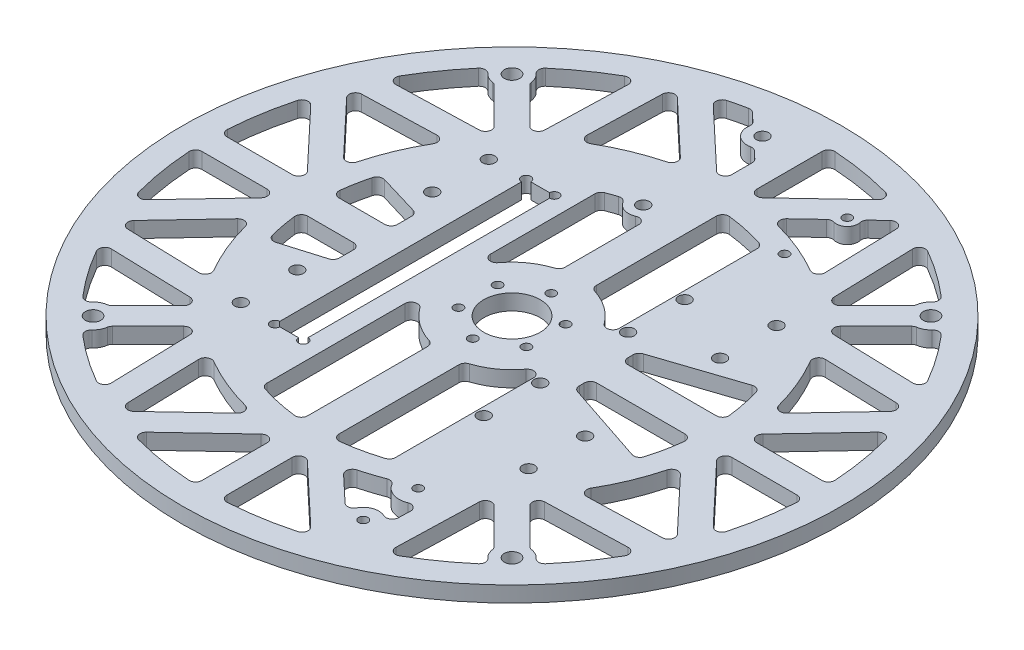
SolidWorks part; units mm, degrees
material "Thornel Mat VMA"
ref_plane "前视基准面" through (0, 0, 0) normal (0, 0, 1) x (1, 0, 0)
ref_plane "上视基准面" through (0, 0, 0) normal (0, 1, 0) x (1, 0, 0)
ref_plane "右视基准面" through (0, 0, 0) normal (1, 0, 0) x (0, 0, -1)
other "Configuration Table"
sketch "草图1" plane through (0, 0, 0) normal (0, 1, 0) x (1, 0, 0)
  circle A0 centre (0, 0) radius 105
  dimension "D1" = 210
extrude "凸台-拉伸1" add sketch "草图1" along normal blind 5
sketch "草图3" plane through (0, 5, 0) normal (0, 1, 0) x (1, 0, 0)
  circle A0 centre (-46.9, -39.5) radius 1.95
  circle A1 centre (-46.9, -21.5) radius 1.95
  circle A2 centre (-46.9, 21.5) radius 1.95
  circle A3 centre (-46.9, 39.5) radius 1.95
  circle A4 centre (23, -32) radius 1.95
  circle A5 centre (23, -14) radius 1.95
  circle A6 centre (44.8, -39.5) radius 1.95
  circle A7 centre (44.8, -21.5) radius 1.95
  circle A8 centre (44.8, 39.5) radius 1.95
  circle A9 centre (44.8, 21.5) radius 1.95
  circle A10 centre (23, 32) radius 1.95
  circle A11 centre (23, 14) radius 1.95
  circle A12 centre (-9.7, 89.516) radius 1.95
  circle A13 centre (-9.7, 51.516) radius 1.95
  circle A14 centre (26.3, 80.516) radius 1.45
  circle A15 centre (32.6, -62.5) radius 1.45
  circle A16 centre (32.6, -80) radius 1.45
  circle A17 centre (26.3, 60.516) radius 1.45
  dimension "D1" = 3.9
  dimension "D2" = 2.9
extrude "切除-拉伸1" cut sketch "草图3" against normal through all
sketch "草图5" plane through (0, 5, 0) normal (0, 1, 0) x (1, 0, 0)
  line L0 (0, 0) -> (0, 105) construction
  circle A0 centre (0, 0) radius 105 construction
sketch "草图6" plane through (0, 0, 0) normal (0, -1, 0) x (1, 0, 0)
  line L1 (-35.5, 40) -> (-26.5, 40)
  line L2 (-35.5, 40) -> (-35.5, -40)
  line L3 (-35.5, -40) -> (-26.5, -40)
  line L4 (-26.5, 40) -> (-26.5, -40)
  point P4 (-26.5, 0)
  dimension "D1" = 9
  dimension "D2" = 80
  dimension "D3" = 26.5
extrude "切除-拉伸2" cut sketch "草图6" against normal through all
sketch "草图7" plane through (0, 5, 0) normal (0, 1, 0) x (1, 0, 0)
  line L0 (0, 0) -> (66.7403, 66.7403) construction
  line L1 (0, 0) -> (94.385, 0) construction
  circle A0 centre (0, 0) radius 94.385 construction
  circle A1 centre (66.7403, 66.7403) radius 2.45
  circle A2 centre (-66.7403, 66.7403) radius 2.45
  circle A3 centre (-66.7403, -66.7403) radius 2.45
  circle A4 centre (66.7403, -66.7403) radius 2.45
  point P15 (0, 0)
  dimension "D2" = 4.9
  dimension "D4" = 188.77
  dimension "D1" = 45
  dimension "D3" = 4
extrude "切除-拉伸3" cut sketch "草图7" against normal through all
sketch "草图8" plane through (0, 5, 0) normal (0, 1, 0) x (1, 0, 0)
  circle A0 centre (0, 0) radius 12.5 construction
  circle A1 centre (0, 12.5) radius 1.45
  circle A2 centre (10.8253, 6.25) radius 1.45
  circle A3 centre (10.8253, -6.25) radius 1.45
  circle A4 centre (0, -12.5) radius 1.45
  circle A5 centre (-10.8253, -6.25) radius 1.45
  circle A6 centre (-10.8253, 6.25) radius 1.45
  point P17 (0, 0)
  dimension "D1" = 25
  dimension "D2" = 2.9
  dimension "D3" = 6
extrude "切除-拉伸4" cut sketch "草图8" against normal through all
sketch "草图10" plane through (0, 0, 0) normal (0, -1, 0) x (1, 0, 0)
  circle A0 centre (0, 0) radius 9
  dimension "D1" = 18
extrude "切除-拉伸5" cut sketch "草图10" against normal through all
sketch "草图9" plane through (0, 0, 0) normal (0, -1, 0) x (1, 0, 0)
  line L0 (-1000, 0) -> (49000, 0) construction
  line L1 (0, -1000) -> (0, 49000) construction
  line L2 (-20.5, 4.5552) -> (-20.5, 59.0424) construction
  line L3 (-5, 62.2997) -> (-5, 20.3961) construction
  line L5 (-62.2997, 5) -> (-43.5, 5) construction
  line L6 (-43.5, 5) -> (-43.5, 13) construction
  line L7 (-43.5, 13) -> (-59.8831, 17.8961) construction
  line L8 (-35.5, 40) -> (-35.5, -40) construction
  line L9 (-66.9512, 61.2944) -> (-51.8909, 46.234) construction
  line L10 (-66.7403, 66.7403) -> (0, 0) construction
  line L11 (-85.8063, 45.2359) -> (-51.8909, 46.234) construction
  line L12 (-89.6163, 37.1203) -> (-58.1614, 38.046) construction
  line L13 (-89.6163, 37.1203) -> (-68.0289, 14.2237) construction
  line L14 (-92.6608, 28.6876) -> (-69.3848, 4) construction
  line L15 (-96.9175, 4) -> (-69.3848, 4)
  line L16 (-96.9175, 4) -> (-69.3848, 4) construction
  line L17 (-69.3848, 4) -> (-92.6608, 28.6876)
  line L18 (-68.0289, 14.2237) -> (-89.6163, 37.1203)
  line L19 (-89.6163, 37.1203) -> (-58.1614, 38.046)
  line L20 (-85.8063, 45.2359) -> (-51.8909, 46.234)
  line L31 (-51.8909, 46.234) -> (-66.9512, 61.2944)
  line L32 (-28.6876, 92.6608) -> (-4, 69.3848)
  line L33 (-4, 69.3848) -> (-4, 96.9175)
  line L34 (-38.046, 58.1614) -> (-37.1203, 89.6163)
  line L35 (-37.1203, 89.6163) -> (-14.2237, 68.0289)
  line L36 (-61.2944, 66.9512) -> (-46.234, 51.8909)
  line L37 (-46.234, 51.8909) -> (-45.2359, 85.8063)
  line L38 (45.2359, 85.8063) -> (46.234, 51.8909)
  line L39 (46.234, 51.8909) -> (61.2944, 66.9512)
  line L40 (14.2237, 68.0289) -> (27.7056, 80.74)
  line L41 (37.4346, 78.9373) -> (37.8257, 65.6467)
  line L42 (4, 96.9175) -> (4, 69.3848)
  line L43 (4, 69.3848) -> (28.6876, 92.6608)
  line L44 (92.6608, 28.6876) -> (69.3848, 4)
  line L45 (69.3848, 4) -> (96.9175, 4)
  line L46 (58.1614, 38.046) -> (89.6163, 37.1203)
  line L47 (89.6163, 37.1203) -> (68.0289, 14.2237)
  line L48 (66.9512, 61.2944) -> (51.8909, 46.234)
  line L49 (51.8909, 46.234) -> (85.8063, 45.2359)
  line L50 (85.8063, -45.2359) -> (51.8909, -46.234)
  line L51 (51.8909, -46.234) -> (66.9512, -61.2944)
  line L52 (68.0289, -14.2237) -> (89.6163, -37.1203)
  line L53 (89.6163, -37.1203) -> (58.1614, -38.046)
  line L54 (96.9175, -4) -> (69.3848, -4)
  line L55 (69.3848, -4) -> (92.6608, -28.6876)
  line L56 (28.6876, -92.6608) -> (4, -69.3848)
  line L57 (4, -69.3848) -> (4, -96.9175)
  line L58 (38.046, -58.1614) -> (37.1203, -89.6163)
  line L59 (37.1203, -89.6163) -> (29.2913, -82.2349)
  line L60 (61.2944, -66.9512) -> (46.234, -51.8909)
  line L61 (46.234, -51.8909) -> (45.2359, -85.8063)
  line L62 (-45.2359, -85.8063) -> (-46.234, -51.8909)
  line L63 (-46.234, -51.8909) -> (-61.2944, -66.9512)
  line L64 (-14.2237, -68.0289) -> (-37.1203, -89.6163)
  line L65 (-37.1203, -89.6163) -> (-38.046, -58.1614)
  line L67 (-4, -69.3848) -> (-28.6876, -92.6608)
  line L68 (-92.6608, -28.6876) -> (-69.3848, -4)
  line L69 (-69.3848, -4) -> (-96.9175, -4)
  line L70 (-58.1614, -38.046) -> (-89.6163, -37.1203)
  line L71 (-89.6163, -37.1203) -> (-68.0289, -14.2237)
  line L72 (-66.9512, -61.2944) -> (-51.8909, -46.234)
  line L73 (-51.8909, -46.234) -> (-85.8063, -45.2359)
  line L74 (24.4081, -77.631) -> (14.2237, -68.0289)
  line L75 (-4, -81.3931) -> (-4, -69.3848)
  line L76 (-4, -96.9175) -> (-4, -93.7492) [skipped]
  line L77 (-62.2997, 5) -> (-43.5, 5)
  line L78 (-43.5, 5) -> (-43.5, 13)
  line L79 (-43.5, 13) -> (-59.8831, 17.8961)
  line L80 (-20.5, 59.0424) -> (-20.5, 4.5552)
  line L81 (-5, 62.2997) -> (-5, 20.3961)
  line L82 (20.5, 59.0424) -> (20.5, 4.5552)
  line L83 (5, 62.2997) -> (5, 20.3961)
  line L84 (20.5, -59.0424) -> (20.5, -4.5552)
  line L85 (5, -62.2997) -> (5, -20.3961)
  line L86 (-20.5, -48.2466) -> (-20.5, -4.5552)
  line L87 (-5, -51.516) -> (-5, -20.3961)
  line L88 (-43.5, -5) -> (-43.5, -13)
  line L89 (-62.2997, -5) -> (-43.5, -5)
  line L90 (-43.5, -13) -> (-59.8831, -17.8961)
  line L91 (30, 5) -> (62.2997, 5)
  line L92 (30, 5) -> (30, 10)
  line L93 (30, 10) -> (59.2927, 19.7642)
  line L94 (30, -10) -> (59.2927, -19.7642)
  line L95 (30, -5) -> (30, -10)
  line L96 (30, -5) -> (62.2997, -5)
  line L97 (-4, -81.3931) -> (-7.7774, -84.9546)
  line L98 (-14.3666, -91.1669) -> (-18.6366, -95.1928)
  circle A1 centre (0, 0) radius 21 construction
  arc A2 (0, -62.5) -> (-59.8831, -17.8961) centre (0, 0) ccw construction
  arc A3 (26.7287, 64.1547) -> (38.0725, 58.1441) centre (0, 0) ccw construction
  arc A4 (-5, -51.516) -> (-14.2752, -50.4401) centre (-9.7, -51.516) ccw
  arc A5 (-71.9303, 65.0771) -> (-71.9303, -65.0771) centre (0, 0) ccw construction
  circle A6 centre (-66.7403, 66.7403) radius 5.45
  arc A7 (-61.2944, 66.9512) -> (-65.0771, 71.9303) centre (-66.7403, 66.7403) ccw
  circle A8 centre (0, 0) radius 105 construction
  arc A17 (-58.1614, 38.046) -> (-68.0289, 14.2237) centre (0, 0) ccw
  arc A18 (-92.6608, 28.6876) -> (-96.9175, 4) centre (0, 0) ccw
  arc A19 (-71.9303, 65.0771) -> (-85.8063, 45.2359) centre (0, 0) ccw
  arc A20 (-14.2237, 68.0289) -> (-38.046, 58.1614) centre (0, 0) ccw
  arc A21 (-45.2359, 85.8063) -> (-65.0771, 71.9303) centre (0, 0) ccw
  arc A22 (-4, 96.9175) -> (-28.6876, 92.6608) centre (0, 0) ccw
  arc A24 (28.6876, 92.6608) -> (4, 96.9175) centre (0, 0) ccw
  arc A25 (65.0771, 71.9303) -> (45.2359, 85.8063) centre (0, 0) ccw
  arc A26 (68.0289, 14.2237) -> (58.1614, 38.046) centre (0, 0) ccw
  arc A27 (85.8063, 45.2359) -> (71.9303, 65.0771) centre (0, 0) ccw
  arc A28 (96.9175, 4) -> (92.6608, 28.6876) centre (0, 0) ccw
  arc A29 (58.1614, -38.046) -> (68.0289, -14.2237) centre (0, 0) ccw
  arc A30 (92.6608, -28.6876) -> (96.9175, -4) centre (0, 0) ccw
  arc A31 (71.9303, -65.0771) -> (85.8063, -45.2359) centre (0, 0) ccw
  arc A32 (14.2237, -68.0289) -> (38.046, -58.1614) centre (0, 0) ccw
  arc A33 (45.2359, -85.8063) -> (65.0771, -71.9303) centre (0, 0) ccw
  arc A34 (4, -96.9175) -> (28.6876, -92.6608) centre (0, 0) ccw
  arc A35 (-38.046, -58.1614) -> (-14.2237, -68.0289) centre (0, 0) ccw
  arc A36 (-28.6876, -92.6608) -> (-18.6366, -95.1928) centre (0, 0) ccw
  arc A37 (-65.0771, -71.9303) -> (-45.2359, -85.8063) centre (0, 0) ccw
  arc A38 (-68.0289, -14.2237) -> (-58.1614, -38.046) centre (0, 0) ccw
  arc A39 (-85.8063, -45.2359) -> (-71.9303, -65.0771) centre (0, 0) ccw
  arc A40 (-96.9175, -4) -> (-92.6608, -28.6876) centre (0, 0) ccw
  arc A41 (-14.2752, -50.4401) -> (-20.5, -48.2466) centre (0, 0) cw
  circle A42 centre (66.7403, 66.7403) radius 5.45
  arc A43 (65.0771, 71.9303) -> (61.2944, 66.9512) centre (66.7403, 66.7403) ccw
  arc A44 (-7.7774, -84.9546) -> (-14.3666, -91.1669) centre (-9.7, -89.516) ccw
  circle A45 centre (-66.7403, -66.7403) radius 5.45
  arc A46 (-65.0771, -71.9303) -> (-61.2944, -66.9512) centre (-66.7403, -66.7403) ccw
  circle A47 centre (32.6, 80) radius 4.95
  circle A48 centre (66.7403, -66.7403) radius 5.45
  arc A49 (61.2944, -66.9512) -> (65.0771, -71.9303) centre (66.7403, -66.7403) ccw
  arc A50 (27.7056, 80.74) -> (37.4346, 78.9373) centre (32.6, 80) ccw
  circle A51 centre (-9.7, -89.516) radius 1.95 construction
  circle A52 centre (32.6, 62.5) radius 1.45 construction
  circle A58 centre (26.3, -80.516) radius 3.45
  arc A59 (29.2913, -82.2349) -> (24.4081, -77.631) centre (26.3, -80.516) ccw
  arc A60 (-66.742, 70.3883) -> (-71.3594, 65.7026) centre (0, 0) ccw construction
  arc A61 (-71.9303, 65.0771) -> (-66.9512, 61.2944) centre (-66.7403, 66.7403) ccw
  arc A62 (26.7287, 64.1547) -> (14.2237, 68.0289) centre (0, 0) ccw
  arc A63 (37.8257, 65.6467) -> (26.7287, 64.1547) centre (32.6, 62.5) ccw
  arc A64 (38.0725, 58.1441) -> (37.3484, 58.6119) centre (0, 0) ccw [skipped]
  arc A65 (65.0771, 71.9303) -> (-65.0771, 71.9303) centre (0, 0) ccw construction
  arc A66 (66.9512, 61.2944) -> (71.9303, 65.0771) centre (66.7403, 66.7403) ccw
  arc A67 (71.9303, -65.0771) -> (66.9512, -61.2944) centre (66.7403, -66.7403) ccw
  arc A68 (71.9303, -65.0771) -> (71.9303, 65.0771) centre (0, 0) ccw construction
  arc A69 (0, -97) -> (65.0771, -71.9303) centre (0, 0) ccw construction
  arc A70 (-71.3594, -65.7026) -> (-65.7026, -71.3594) centre (0, 0) ccw construction
  arc A71 (-66.9512, -61.2944) -> (-71.9303, -65.0771) centre (-66.7403, -66.7403) ccw
  arc A72 (-65.0771, -71.9303) -> (-18.6366, -95.1928) centre (0, 0) ccw construction
  arc A73 (-59.8831, 17.8961) -> (-62.2997, 5) centre (0, 0) ccw
  arc A74 (-20.5, 59.0424) -> (-5, 62.2997) centre (0, 0) cw
  arc A75 (-20.5, 4.5552) -> (-5, 20.3961) centre (0, 0) cw
  arc A76 (20.5, 59.0424) -> (5, 62.2997) centre (0, 0) ccw
  arc A77 (20.5, 4.5552) -> (5, 20.3961) centre (0, 0) ccw
  arc A78 (20.5, -4.5552) -> (5, -20.3961) centre (0, 0) cw
  arc A79 (20.5, -59.0424) -> (5, -62.2997) centre (0, 0) cw
  arc A81 (-20.5, -4.5552) -> (-5, -20.3961) centre (0, 0) ccw
  arc A82 (-59.8831, -17.8961) -> (-62.2997, -5) centre (0, 0) cw
  circle A83 centre (23, 14) radius 1.95 construction
  arc A84 (59.2927, 19.7642) -> (62.2997, 5) centre (0, 0) cw
  arc A85 (59.2927, -19.7642) -> (62.2997, -5) centre (0, 0) ccw
  dimension "D1" = 42
  dimension "D2" = 125
  dimension "D5" = 7
  dimension "D10" = 8
  dimension "D20" = 6.1
  dimension "D21" = 3
  dimension "D3" = 9.1104
  dimension "D4" = 5
  dimension "D6" = 5
  dimension "D7" = 8
  dimension "D8" = 8
  dimension "D11" = 8
  dimension "D12" = 8
  dimension "D13" = 4
  dimension "D14" = 8
  dimension "D15" = 4
  dimension "D16" = 3
  dimension "D17" = 3
  dimension "D23" = 7
  dimension "D24" = 5
  dimension "D25" = 2
  dimension "D9" = 3
  dimension "D18" = 3
  dimension "D19" = 3.5
  dimension "D22" = 2
extrude "切除-拉伸7" cut sketch "草图9" against normal through all
fillet "圆角3" radius 2 82 edges at (-20.5, 2.5, 4.5552) (-5, 2.5, 62.2997) (-5, 2.5, 20.3961) (-96.9175, 2.5, -4) (-69.3848, 2.5, -4) (-14.2237, 2.5, -68.0289) (-28.6876, 2.5, -92.6608) (-4, 2.5, -69.3848) (-45.2359, 2.5, -85.8063) (-65.0771, 2.5, -71.9303) (-61.2944, 2.5, -66.9512) (28.6876, 2.5, -92.6608) (58.1614, 2.5, -38.046) (68.0289, 2.5, -14.2237) (89.6163, 2.5, -37.1203) (92.6608, 2.5, -28.6876) (96.9175, 2.5, -4) (-43.5, 2.5, -5) (-43.5, 2.5, -13) (-59.8831, 2.5, -17.8961) (-62.2997, 2.5, -5) (59.2927, 2.5, 19.7642) (62.2997, 2.5, 5) (30, 2.5, 5) (30, 2.5, -5) (62.2997, 2.5, -5) (59.2927, 2.5, -19.7642) (30, 2.5, -10) (-85.8063, 2.5, -45.2359) (-66.9512, 2.5, -61.2944) (-71.9303, 2.5, -65.0771) (20.5, 2.5, 59.0424) (20.5, 2.5, 4.5552) (5, 2.5, 62.2997) (5, 2.5, -20.3961) (20.5, 2.5, -4.5552) (20.5, 2.5, -59.0424) (-92.6608, 2.5, 28.6876) (-96.9175, 2.5, 4) (-4, 2.5, 69.3848) (-28.6876, 2.5, 92.6608) (-14.2237, 2.5, 68.0289) (-38.046, 2.5, 58.1614) (-37.1203, 2.5, 89.6163) (-45.2359, 2.5, 85.8063) (-46.234, 2.5, 51.8909) (-61.2944, 2.5, 66.9512) (-65.0771, 2.5, 71.9303) (14.2237, 2.5, 68.0289) (27.7056, 2.5, 80.74) (37.4346, 2.5, 78.9373) (37.8257, 2.5, 65.6467) (-43.5, 2.5, 13) (-62.2997, 2.5, 5) (-51.8909, 2.5, 46.234) (-85.8063, 2.5, 45.2359) (-66.9512, 2.5, 61.2944) (-89.6163, 2.5, 37.1203) (24.4081, 2.5, -77.631) (14.2237, 2.5, -68.0289) (38.046, 2.5, -58.1614) (37.1203, 2.5, -89.6163) (29.2913, 2.5, -82.2349) (65.0771, 2.5, -71.9303) (45.2359, 2.5, -85.8063) (51.8909, 2.5, 46.234) (71.9303, 2.5, 65.0771) (58.1614, 2.5, 38.046) (89.6163, 2.5, 37.1203) (66.9512, 2.5, -61.2944) (85.8063, 2.5, -45.2359) (45.2359, 2.5, 85.8063) (65.0771, 2.5, 71.9303) (69.3848, 2.5, 4) (92.6608, 2.5, 28.6876) (-71.9303, 2.5, 65.0771) (-7.7774, 2.5, -84.9546) (-14.3666, 2.5, -91.1669) (-18.6366, 2.5, -95.1928) (-14.2752, 2.5, -50.4401) (-5, 2.5, -51.516) (-20.5, 2.5, -48.2466)
sketch "草图11" plane through (0, 0, 0) normal (0, -1, 0) x (1, 0, 0)
  circle A0 centre (-35.5, 40) radius 1.5
  circle A1 centre (-26.5, 40) radius 1.5
  circle A2 centre (-35.5, -40) radius 1.5
  circle A3 centre (-26.5, -40) radius 1.5
  dimension "D1" = 3
extrude "切除-拉伸8" cut sketch "草图11" against normal through all
